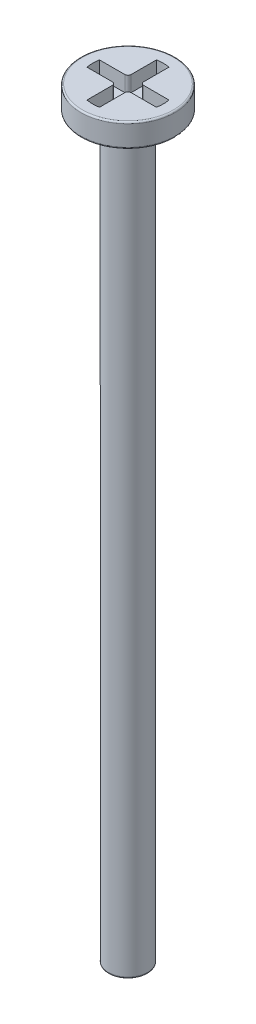
SolidWorks part; units mm, degrees
ref_plane "Front Plane" through (0, 0, 0) normal (0, 0, 1) x (1, 0, 0)
ref_plane "Top Plane" through (0, 0, 0) normal (0, 1, 0) x (1, 0, 0)
ref_plane "Right Plane" through (0, 0, 0) normal (1, 0, 0) x (0, 0, -1)
sketch "Sketch1" plane through (0, 0, 0) normal (0, 0, 1) x (1, 0, 0)
  line L0 (0, 0) -> (-3, 0)
  line L1 (-3, 0) -> (-3, -1.5)
  line L2 (-3, -1.5) -> (-1.25, -1.5)
  line L3 (-1.25, -1.5) -> (-1.25, -48.5)
  line L4 (-1.25, -48.5) -> (0, -48.5)
  line L5 (0, -48.5) -> (0, 0)
  line L6 (0, 14.9129) -> (0, 0) construction
  dimension "D1" = 2.5
  dimension "D2" = 3
  dimension "D3" = 3
  dimension "D4" = 1.5
  dimension "D5" = 47
revolve "Revolve1" add sketch "Sketch1" angle 360 about L6
fillet "Fillet1" radius 0.1 3 edges at (0, -48.5, 1.25) (0, 0, 3) (0, -1.5, 3)
sketch "Sketch2" plane through (0, 0, 0) normal (0, 1, 0) x (1, 0, 0)
  line L0 (0, 2.25) -> (0, -2.25) construction
  line L1 (-2.25, 0) -> (2.25, 0) construction
  line L2 (-2.2142, -0.4) -> (-0.6, -0.4)
  line L3 (-2.2142, 0.4) -> (-0.6, 0.4)
  line L4 (-0.4, 2.2142) -> (-0.4, 0.6)
  line L5 (0.4, 2.2142) -> (0.4, 0.6)
  line L6 (-0.4, 2.25) -> (-0.4, -2.25) construction
  line L7 (0.4, 2.25) -> (0.4, -2.25) construction
  line L8 (-2.25, -0.4) -> (2.25, -0.4) construction
  line L9 (-2.25, 0.4) -> (2.25, 0.4) construction
  line L10 (0.6, 0.4) -> (2.2142, 0.4)
  line L11 (0.4, -0.6) -> (0.4, -2.2142)
  line L12 (-0.4, -0.6) -> (-0.4, -2.2142)
  line L13 (0.6, -0.4) -> (2.2142, -0.4)
  arc A0 (-2.2142, 0.4) -> (-2.2142, -0.4) centre (0, 0) ccw
  arc A1 (0.4, 2.2142) -> (-0.4, 2.2142) centre (0, 0) ccw
  arc A2 (-0.4, -2.2142) -> (0.4, -2.2142) centre (0, 0) ccw
  arc A3 (2.2142, -0.4) -> (2.2142, 0.4) centre (0, 0) ccw
  arc A4 (-0.6, -0.4) -> (-0.4, -0.6) centre (-0.6, -0.6) cw
  arc A5 (0.4, -0.6) -> (0.6, -0.4) centre (0.6, -0.6) cw
  arc A6 (0.6, 0.4) -> (0.4, 0.6) centre (0.6, 0.6) cw
  arc A7 (-0.4, 0.6) -> (-0.6, 0.4) centre (-0.6, 0.6) cw
  dimension "D1" = 4.5
  dimension "D6" = 0.2
  dimension "D2" = 0.4
  dimension "D3" = 0.4
  dimension "D4" = 0.4
  dimension "D5" = 0.4
extrude "Cut-Extrude1" cut sketch "Sketch2" against normal blind 1
